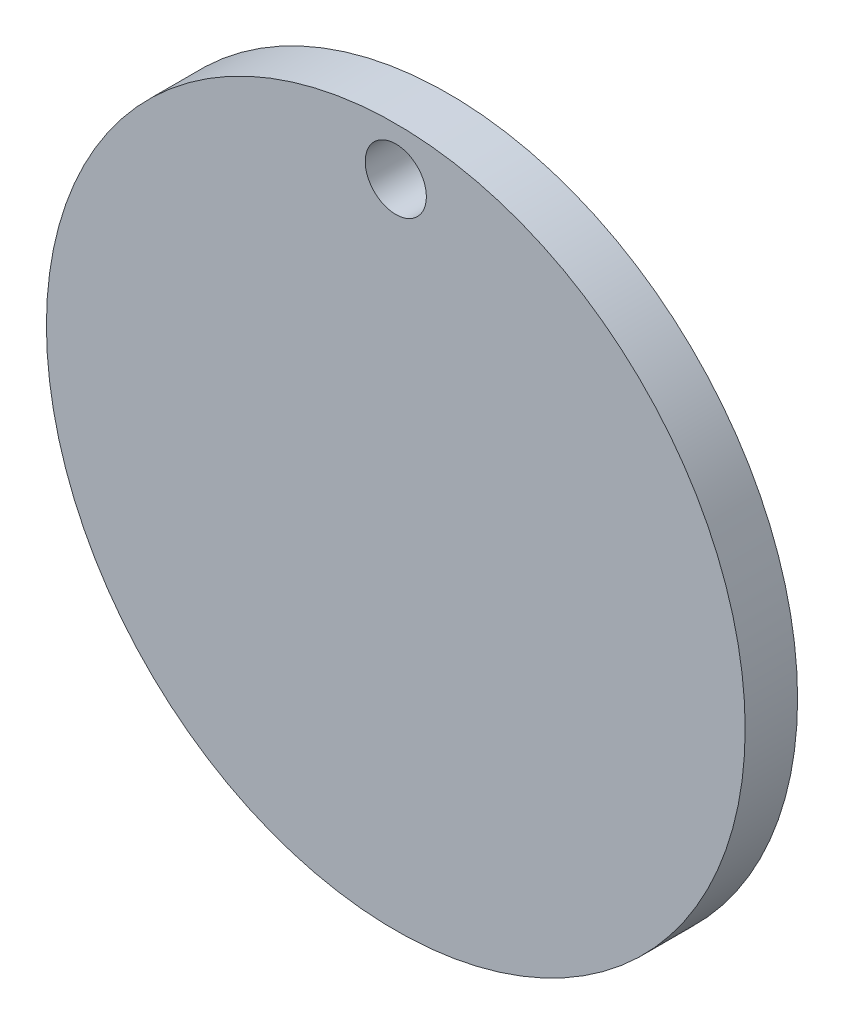
SolidWorks part; units mm, degrees
ref_plane "前视基准面" through (0, 0, 0) normal (0, 0, 1) x (1, 0, 0)
ref_plane "上视基准面" through (0, 0, 0) normal (0, 1, 0) x (1, 0, 0)
ref_plane "右视基准面" through (0, 0, 0) normal (1, 0, 0) x (0, 0, -1)
sketch "草图1" plane through (0, 0, 0) normal (0, 0, 1) x (1, 0, 0)
  circle A0 centre (0, 0) radius 20
extrude "凸台-拉伸1" add sketch "草图1" along normal blind 3
sketch "草图2" plane through (0, 0, 3) normal (0, 0, 1) x (1, 0, 0)
  circle A1 centre (0, 17.25) radius 1.75
extrude "切除-拉伸1" cut sketch "草图2" against normal blind 3
